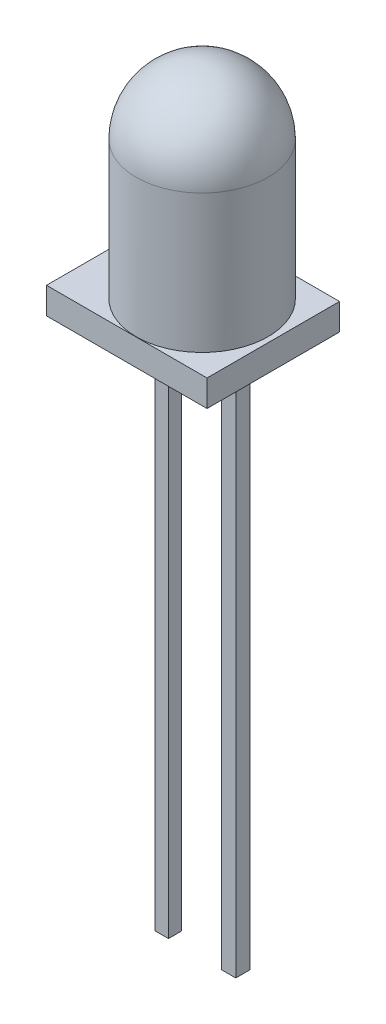
SolidWorks part; units mm, degrees
ref_plane "Front Plane" through (0, 0, 0) normal (0, 0, 1) x (1, 0, 0)
ref_plane "Top Plane" through (0, 0, 0) normal (0, 1, 0) x (1, 0, 0)
ref_plane "Right Plane" through (0, 0, 0) normal (1, 0, 0) x (0, 0, -1)
sketch "Sketch1" plane through (0, 0, 0) normal (0, 0, 1) x (1, 0, 0)
  line L0 (2.49, 0) -> (0, 0)
  line L2 (2.49, 0) -> (2.49, -5.21)
  line L3 (2.49, -5.21) -> (0, -5.21)
  line L4 (0, 2.49) -> (0, -5.21)
  arc A0 (2.49, 0) -> (0, 2.49) centre (0, 0) ccw
  dimension "D1" = 2.49
  dimension "D2" = 7.7
revolve "Revolve3" add sketch "Sketch1" angle 360 about L4
sketch "Sketch2" plane through (0, 0, 0) normal (0, 0, 1) x (1, 0, 0)
  line L0 (0, 2.49) -> (0, -7.9659) construction
  line L1 (-2.49, -5.21) -> (2.49, -5.21) construction
  line L2 (2.6845, -5.21) -> (-3.3733, -5.21)
  line L3 (2.6845, -5.21) -> (2.6845, -6.21)
  line L4 (2.6845, -6.21) -> (-3.3733, -6.21)
  line L5 (-3.3733, -5.21) -> (-3.3733, -6.21)
  line L6 (0, 2.49) -> (2.6845, 2.49) construction
  arc A0 (2.49, 0) -> (-2.49, 0) centre (0, 0) ccw construction
  dimension "D1" = 8.7
  dimension "D2" = 1
  dimension "D3" = 3.3733
extrude "Boss-Extrude2" add sketch "Sketch2" against normal mid plane 5
sketch "Sketch4" plane through (0, -6.21, 0) normal (0, -1, 0) x (1, 0, 0)
  line L0 (0, 0) -> (0, 2.5) construction
  line L1 (-3.3733, 2.5) -> (2.6845, 2.5) construction
  line L2 (0, 0) -> (0, -2.4782) construction
  line L3 (-3.3733, 0) -> (2.6845, 0) construction
  line L4 (-3.3733, -2.5) -> (-3.3733, 2.5) construction
  line L5 (2.6845, -2.5) -> (2.6845, 2.5) construction
  line L7 (-1.52, -0.25) -> (-1.02, -0.25)
  line L8 (-1.52, -0.25) -> (-1.52, 0.25)
  line L9 (-1.52, 0.25) -> (-1.02, 0.25)
  line L10 (-1.02, -0.25) -> (-1.02, 0.25)
  line L11 (-1.52, -0.25) -> (-1.02, 0.25) construction
  line L12 (-1.52, 0.25) -> (-1.02, -0.25) construction
  line L13 (1.0022, -0.2678) -> (1.5378, -0.2678)
  line L14 (1.0022, -0.2678) -> (1.0022, 0.2678)
  line L15 (1.0022, 0.2678) -> (1.5378, 0.2678)
  line L16 (1.5378, -0.2678) -> (1.5378, 0.2678)
  line L17 (1.0022, -0.2678) -> (1.5378, 0.2678) construction
  line L18 (1.0022, 0.2678) -> (1.5378, -0.2678) construction
  point P12 (-1.27, 0)
  point P17 (1.27, 0)
  dimension "D1" = 0.5
  dimension "D2" = 0.5357
  dimension "D3" = 1.27
  dimension "D4" = 2.54
extrude "Boss-Extrude3" add sketch "Sketch4" along normal blind 20.3
